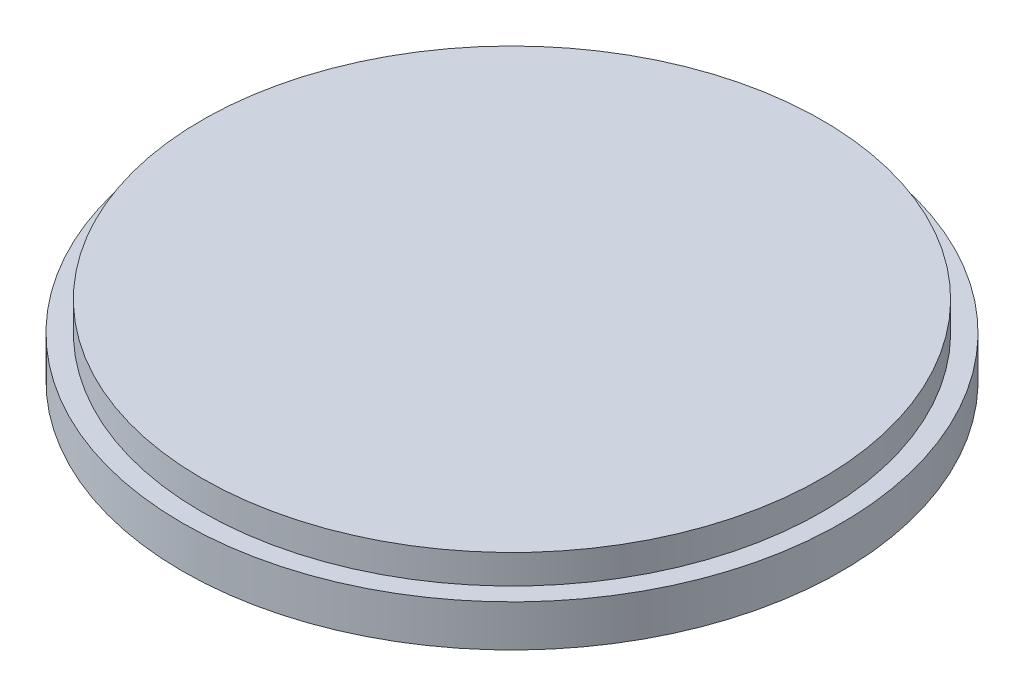
SolidWorks part; units mm, degrees
ref_plane "Front Plane" through (0, 0, 0) normal (0, 0, 1) x (1, 0, 0)
ref_plane "Top Plane" through (0, 0, 0) normal (0, 1, 0) x (1, 0, 0)
ref_plane "Right Plane" through (0, 0, 0) normal (1, 0, 0) x (0, 0, -1)
sketch "Sketch1" plane through (0, 0, 0) normal (0, 0, 1) x (1, 0, 0)
  line L0 (0, -12.9) -> (0, -7.3) construction
  line L1 (0, -12.9) -> (-26.5, -12.9) construction
  line L2 (-26.5, -12.9) -> (-26.5, -7.3) construction
  line L3 (-26.5, -7.3) -> (-34, -4.3)
  line L4 (-34, -4.3) -> (-34, 0)
  line L5 (-34, 0) -> (0, 0)
  line L6 (-26.5, -7.3) -> (0, -7.3)
  line L7 (0, -7.3) -> (0, 0)
  point P4 (0, 0)
  dimension "D1" = 26.5
  dimension "D2" = 5.6
  dimension "D3" = 3
  dimension "D4" = 4.3
  dimension "D5" = 34
revolve "Revolve1" add sketch "Sketch1" angle 360 about L7
sketch "Sketch2" plane through (0, 0, 0) normal (0, 1, 0) x (1, 0, 0)
  circle A2 centre (0, 0) radius 32
  circle A3 centre (0, 0) radius 32
  dimension "D1" = 2
extrude "Boss-Extrude1" add sketch "Sketch2" along normal blind 3
sketch "Sketch3" plane through (0, -7.3, 0) normal (0, -1, 0) x (1, 0, 0)
  line L0 (-15.5563, -15.5563) -> (15.5563, 15.5563) construction
  line L1 (15.5563, -15.5563) -> (-15.5563, 15.5563) construction
  line L2 (0, 0) -> (0, 22) construction
  circle A0 centre (0, 0) radius 22 construction
  point P5 (0, 0)
  point P8 (0, 0)
  dimension "D1" = 44
  dimension "D2" = 45
hole_wizard "M3 Clearance Hole1" positions "Sketch4" profile "Sketch5" hole size "M3" standard "ANSI Metric"
sketch "Sketch4" plane through (0, -7.3, 0) normal (0, -1, 0) x (-1, 0, 0)
  point P0 (15.5563, -15.5563)
  point P3 (15.5563, 15.5563)
  point P6 (-15.5563, 15.5563)
  point P9 (-15.5563, -15.5563)
sketch "Sketch5" plane through (-15.5563, -7.3, 15.5563) normal (1, 0, 0) x (0, 0, -1)
  line L0 (0, 0) -> (0, 5.0215)
  line L1 (0, 5.0215) -> (1.7, 4)
  line L2 (1.7, 4) -> (1.7, 0)
  line L5 (1.7, 0) -> (0, 0)
  line L10 (0, 5.0215) -> (-1.7, 4) construction
  line L11 (0, -6.35) -> (0, 107.95) construction
  dimension "Hole Dia." = 3.4
  dimension "Hole Depth" = 4
  dimension "Drill Angle" = 118
